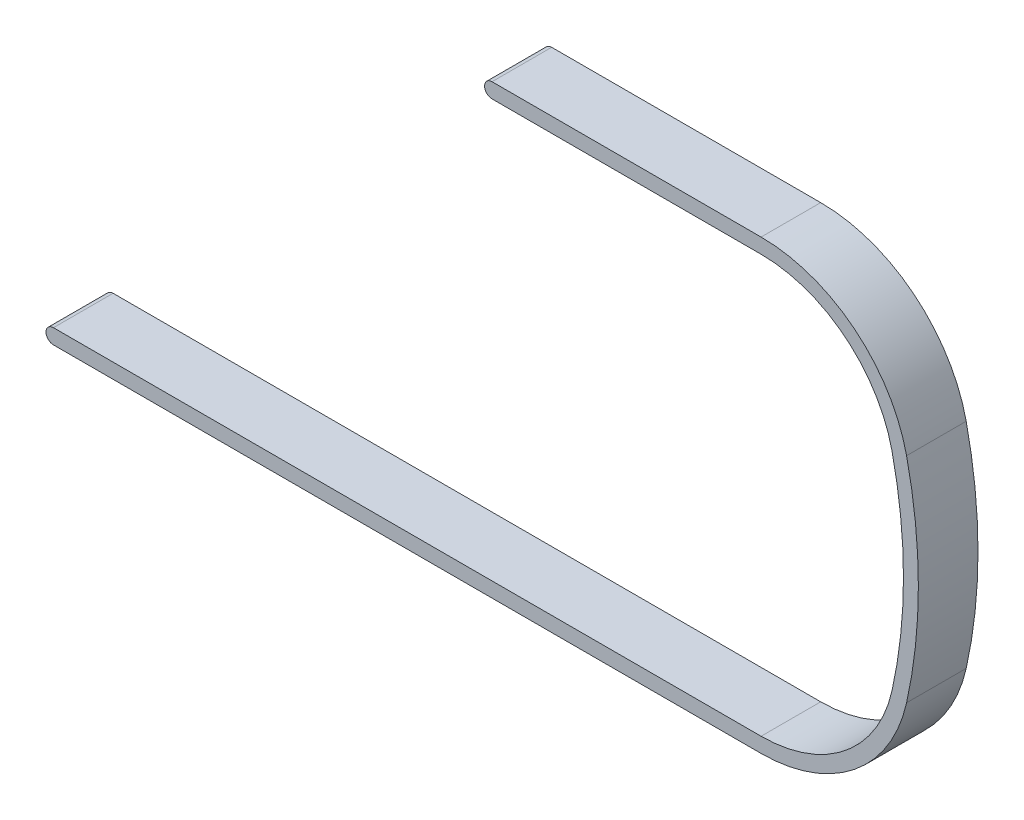
SolidWorks part; units mm, degrees
material "Ductile Iron"
ref_plane "Front Plane" through (0, 0, 0) normal (0, 0, 1) x (1, 0, 0)
ref_plane "Top Plane" through (0, 0, 0) normal (0, 1, 0) x (1, 0, 0)
ref_plane "Right Plane" through (0, 0, 0) normal (1, 0, 0) x (0, 0, -1)
sketch "Sketch1" plane through (0, 0, 0) normal (0, 0, 1) x (1, 0, 0)
  line L1 (-5.8023, 50) -> (174.6792, 50)
  line L3 (-300, -250) -> (174.6792, -250)
  line L6 (-5.8023, 40) -> (174.6792, 40)
  line L7 (-300, -240) -> (174.6792, -240)
  arc A8 (272.2778, -28.2167) -> (272.2778, -171.7833) centre (-49.3419, -100) cw
  arc A9 (174.6792, -250) -> (272.2778, -171.7833) centre (174.6792, -150) ccw
  arc A10 (174.6792, 50) -> (272.2778, -28.2167) centre (174.6792, -50) cw
  arc A11 (174.6792, 40) -> (262.518, -30.395) centre (174.6792, -50) cw
  arc A12 (262.518, -30.395) -> (262.518, -169.605) centre (-49.3419, -100) cw
  arc A13 (174.6792, -240) -> (262.518, -169.605) centre (174.6792, -150) ccw
  arc A14 (-5.8023, 50) -> (-5.8023, 40) centre (-5.8023, 45) ccw
  arc A15 (-300, -250) -> (-300, -240) centre (-300, -245) cw
  point P0 (0, 0)
  dimension "D3" = 10
  dimension "D2" = 100
  dimension "D1" = 300
extrude "Boss-Extrude1" add sketch "Sketch1" along normal blind 40
